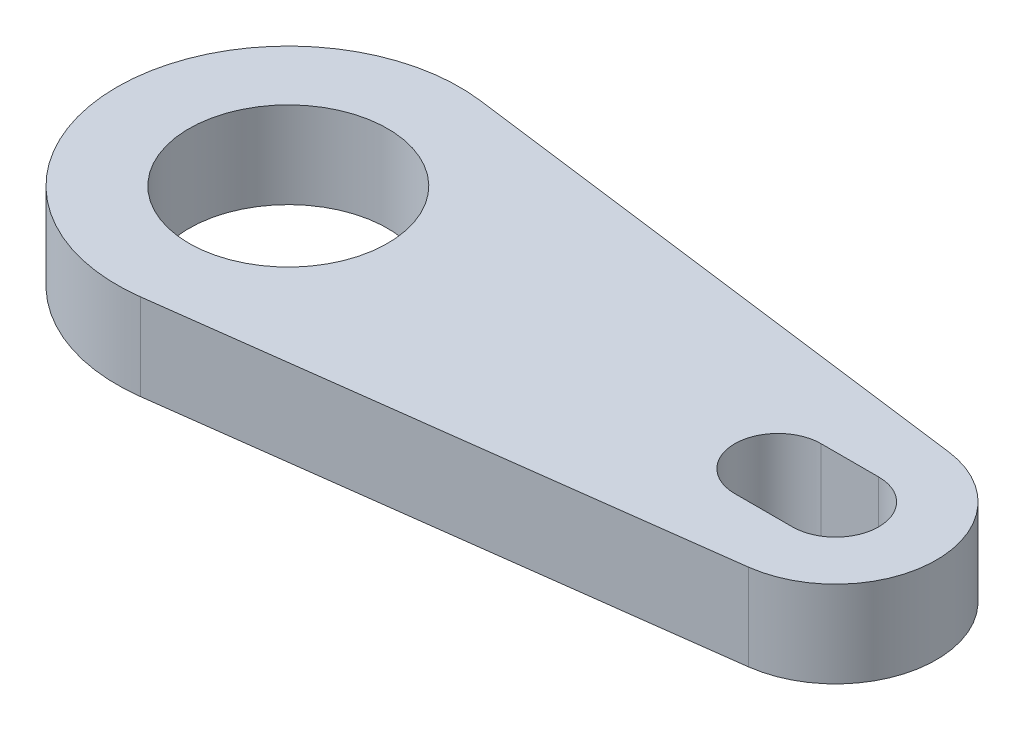
SolidWorks part; units mm, degrees
material "Acrylic (Medium-high impact)"
ref_plane "Plano frontal" through (0, 0, 0) normal (0, 0, 1) x (1, 0, 0)
ref_plane "Plano superior" through (0, 0, 0) normal (0, 1, 0) x (1, 0, 0)
ref_plane "Plano direito" through (0, 0, 0) normal (1, 0, 0) x (0, 0, -1)
sketch "Sketch1" plane through (0, 0, 0) normal (0, 1, 0) x (1, 0, 0)
  line L0 (19.4513, 3.4708) -> (0.7672, 5.9003)
  line L1 (-55, 0) -> (55, 0) construction
  line L2 (19.4513, -3.4708) -> (0.7672, -5.9003)
  line L3 (19, 0) -> (17, 0) construction
  line L4 (19, -1.5) -> (17, -1.5)
  line L5 (19, 1.5) -> (17, 1.5)
  arc A1 (0.7672, 5.9003) -> (0.7672, -5.9003) centre (0, 0) ccw
  arc A2 (19.4513, -3.4708) -> (19.4513, 3.4708) centre (19, 0) ccw
  circle A4 centre (0, 0) radius 3.45
  arc A5 (19, -1.5) -> (19, 1.5) centre (19, 0) ccw
  arc A6 (17, 1.5) -> (17, -1.5) centre (17, 0) ccw
  point P5 (18, 0)
  dimension "D1" = 2.5
  dimension "D2" = 19
  dimension "D3" = 3
  dimension "D4" = 6.9
  dimension "D5" = 5
  dimension "D6" = 2
extrude "Boss-Extrude1" add sketch "Sketch1" along normal mid plane 3
